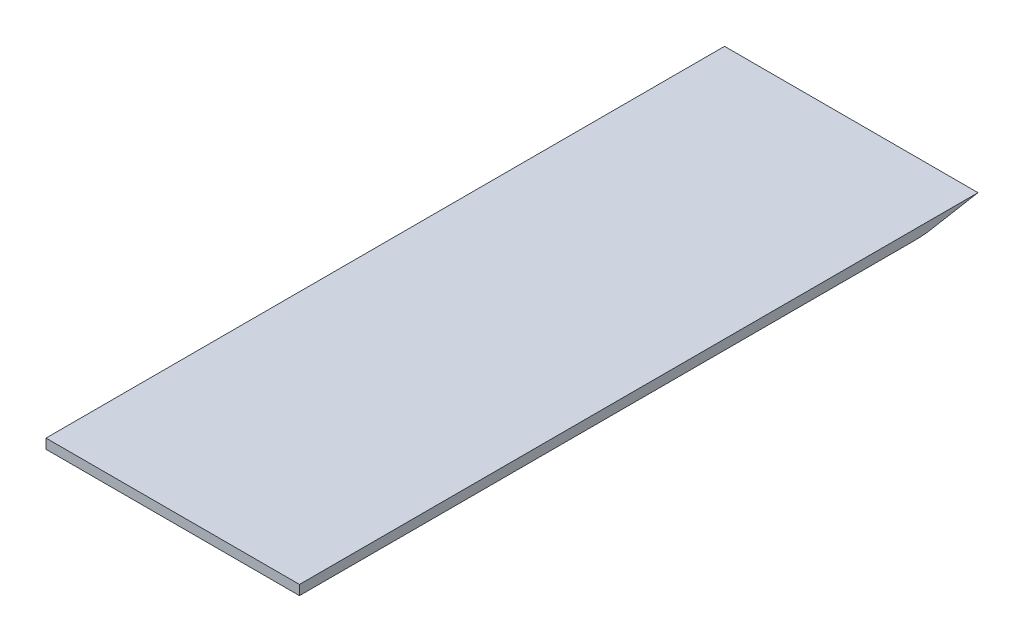
SolidWorks part; units mm, degrees
ref_plane "Front Plane" through (0, 0, 0) normal (0, 0, 1) x (1, 0, 0)
ref_plane "Top Plane" through (0, 0, 0) normal (0, 1, 0) x (1, 0, 0)
ref_plane "Right Plane" through (0, 0, 0) normal (1, 0, 0) x (0, 0, -1)
sketch "Sketch1" plane through (0, 0, 0) normal (1, 0, 0) x (0, 0, -1)
  line L19 (0, 5) -> (0, 0)
  line L20 (0, 0) -> (320, 0)
  line L21 (320, 0) -> (348, 5)
  line L37 (0, 5) -> (348, 5)
  dimension "D1" = 5
  dimension "D8" = 28
  dimension "D9" = 320
extrude "Boss-Extrude1" add sketch "Sketch1" along normal blind 130 contours L19 L20 L21 L37
fillet "Fillet1" radius 50 1 edges at (65, 0, -320)
